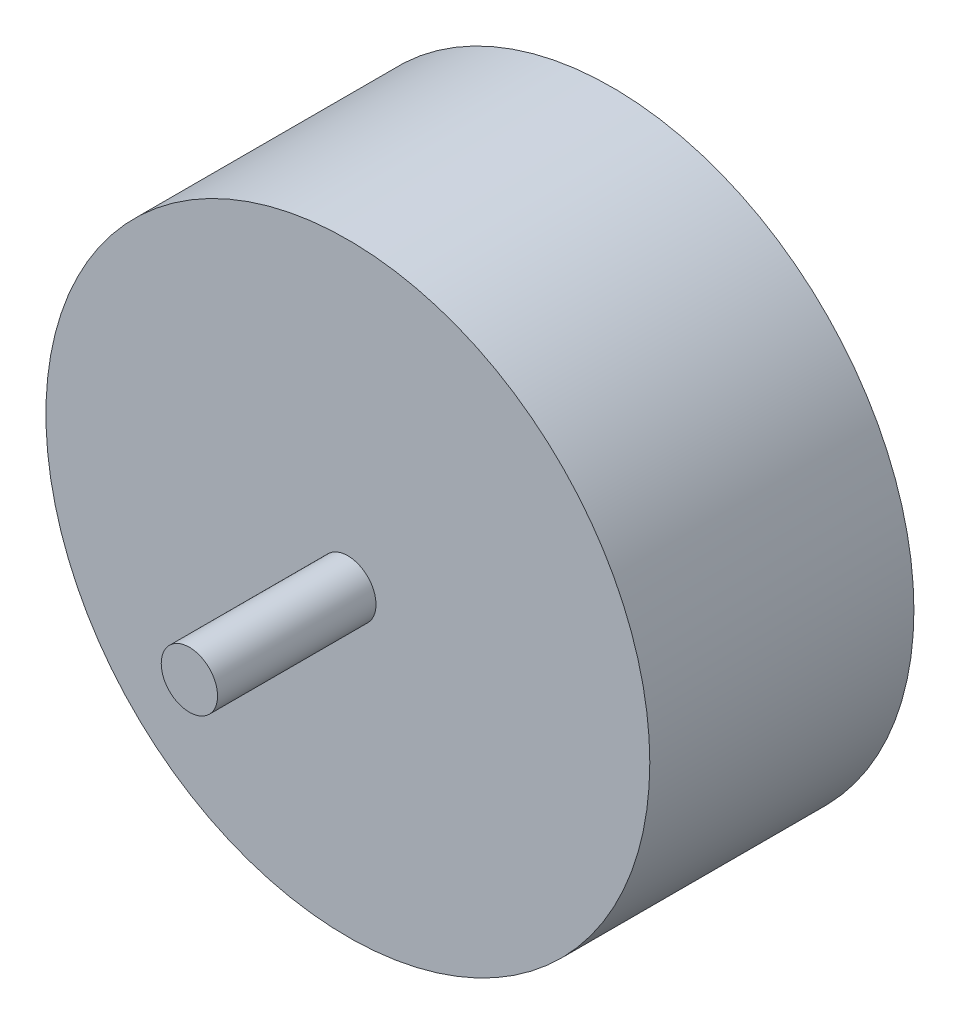
SolidWorks part; units mm, degrees
ref_plane "Front Plane" through (0, 0, 0) normal (0, 0, 1) x (1, 0, 0)
ref_plane "Top Plane" through (0, 0, 0) normal (0, 1, 0) x (1, 0, 0)
ref_plane "Right Plane" through (0, 0, 0) normal (1, 0, 0) x (0, 0, -1)
sketch "Sketch1" plane through (0, 0, 0) normal (0, 0, 1) x (1, 0, 0)
  circle A0 centre (0, 0) radius 85.75
  dimension "D1" = 171.5
extrude "Boss-Extrude1" add sketch "Sketch1" along normal blind 75
sketch "Sketch2" plane through (0, 0, 75) normal (0, 0, 1) x (1, 0, 0)
  circle A0 centre (0, 0) radius 8
  dimension "D1" = 16
extrude "Boss-Extrude2" add sketch "Sketch2" along normal blind 45
